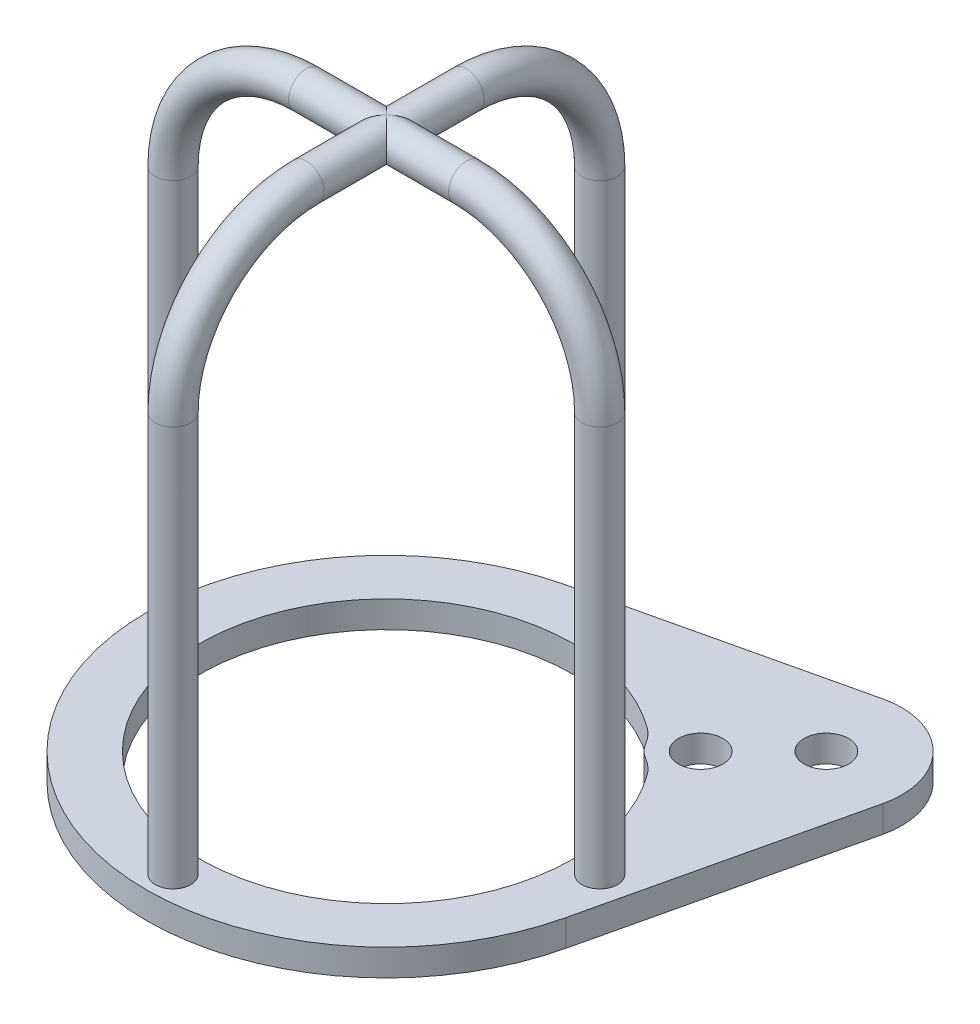
SolidWorks part; units mm, degrees
ref_plane "Plan de face" through (0, 0, 0) normal (0, 0, 1) x (1, 0, 0)
ref_plane "Plan de dessus" through (0, 0, 0) normal (0, 1, 0) x (1, 0, 0)
ref_plane "Plan de droite" through (0, 0, 0) normal (1, 0, 0) x (0, 0, -1)
sketch "Esquisse1" plane through (0, 0, 0) normal (0, 0, 1) x (1, 0, 0)
  line L0 (0, 60) -> (9, 60)
  line L1 (24, 45) -> (24, 0)
  line L2 (0, 0) -> (0, 60) construction
  line L3 (0, 0) -> (24, 0) construction
  arc A0 (24, 45) -> (9, 60) centre (9, 45) ccw
  dimension "D1" = 15
  dimension "D2" = 24
  dimension "D3" = 60
sketch "Esquisse2" plane through (0, 0, 0) normal (0, 1, 0) x (1, 0, 0)
  line L0 (9, 0) -> (24, 0) construction
  line L1 (0, 0) -> (24, 0) construction
  circle A0 centre (24, 0) radius 2
  dimension "D1" = 4
  dimension "D2" = 24
sweep "Balayage1" add profiles "Esquisse2" path "Esquisse1"
sketch "Esquisse3" plane through (0, 0, 0) normal (0, 0, 1) x (1, 0, 0)
  line L0 (0, 0) -> (0, 60) construction
  line L1 (0, 62) -> (0, 58) construction
pattern_circular "Répétition circulaire1" count 4 over 360 about axis through (0, 0, 0) along (0, 1, 0) of "Balayage1"
sketch "Esquisse4" plane through (0, 0, 0) normal (0, -1, 0) x (1, 0, 0)
  line L0 (0, 0) -> (33.2746, -33.2746) construction
  line L1 (0, 0) -> (0, -27) construction
  line L2 (26.2983, 6.1155) -> (33.0278, -22.8235)
  line L3 (22.8235, -33.0278) -> (-6.1155, -26.2983)
  circle A0 centre (0, 0) radius 21 construction
  circle A1 centre (0, 0) radius 27 construction
  circle A2 centre (17.6777, -17.6777) radius 2.5
  circle A3 centre (24.7487, -24.7487) radius 2.5
  arc A4 (33.0278, -22.8235) -> (22.8235, -33.0278) centre (24.7487, -24.7487) cw
  arc A5 (13.4545, -16.1238) -> (16.1238, -13.4545) centre (17.6777, -17.6777) cw
  arc A6 (16.1238, -13.4545) -> (13.4545, -16.1238) centre (0, 0) ccw
  arc A7 (26.2983, 6.1155) -> (-6.1155, -26.2983) centre (0, 0) ccw
  dimension "D1" = 42
  dimension "D2" = 6
  dimension "D3" = 45
  dimension "D6" = 5
  dimension "D7" = 6
  dimension "D8" = 2
  dimension "D4" = 25
  dimension "D5" = 10
extrude "Boss.-Extru.1" add sketch "Esquisse4" along normal blind 3
fillet "Congé1" radius 5 2 edges at (13.4545, -1.5, -16.1238) (16.1238, -1.5, -13.4545)
